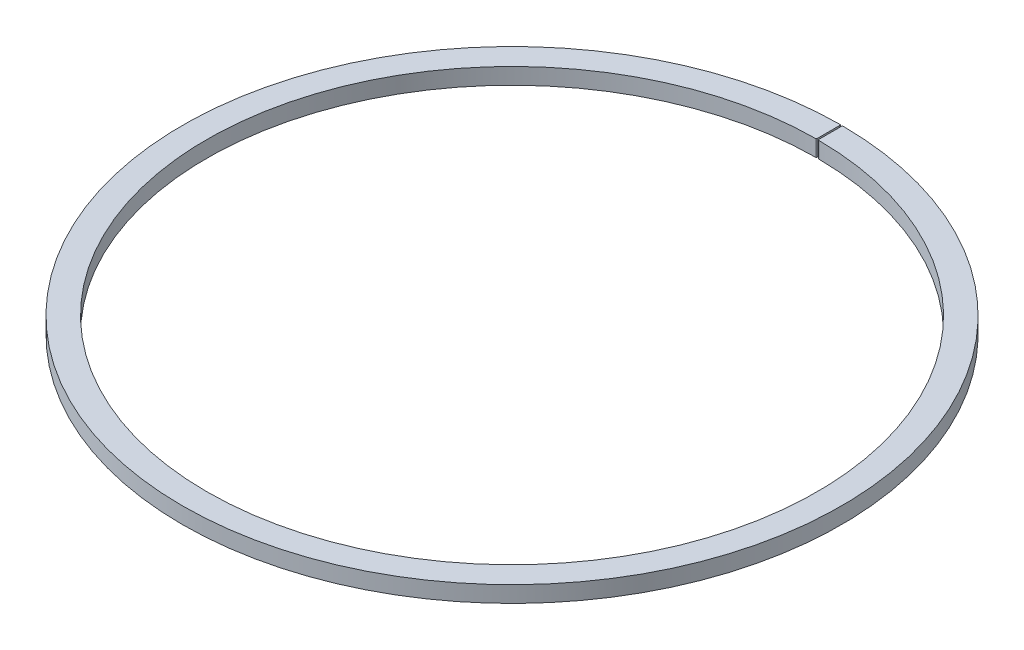
SolidWorks part; units mm, degrees
ref_plane "Front Plane" through (0, 0, 0) normal (0, 0, 1) x (1, 0, 0)
ref_plane "Top Plane" through (0, 0, 0) normal (0, 1, 0) x (1, 0, 0)
ref_plane "Right Plane" through (0, 0, 0) normal (1, 0, 0) x (0, 0, -1)
sketch "Sketch1" plane through (0, 0, 0) normal (0, 1, 0) x (1, 0, 0)
  line L0 (0, 37.5) -> (0, 40.5)
  line L2 (0.1, 41) -> (-0.1, 41)
  line L3 (0.1, 41) -> (0.1, 37)
  line L4 (0.1, 37) -> (-0.1, 37)
  line L5 (-0.1, 41) -> (-0.1, 37)
  line L6 (0, 37) -> (0, 41) construction
  line L7 (0.1, 39) -> (-0.1, 39) construction
  circle A0 centre (0, 0) radius 37.5
  circle A1 centre (0, 0) radius 40.5
  point P6 (0, 39)
  dimension "D1" = 75
  dimension "D2" = 81
  dimension "D3" = 0.2
  dimension "D4" = 4
extrude "Boss-Extrude1" add sketch "Sketch1" along normal blind 2 contours L5 A1 L3 A0
fillet "Fillet1" radius 0.1 4 edges at (0.1, 1, -37.4999) (-0.1, 1, -37.4999) (0.1, 1, -40.4999) (-0.1, 1, -40.4999)
